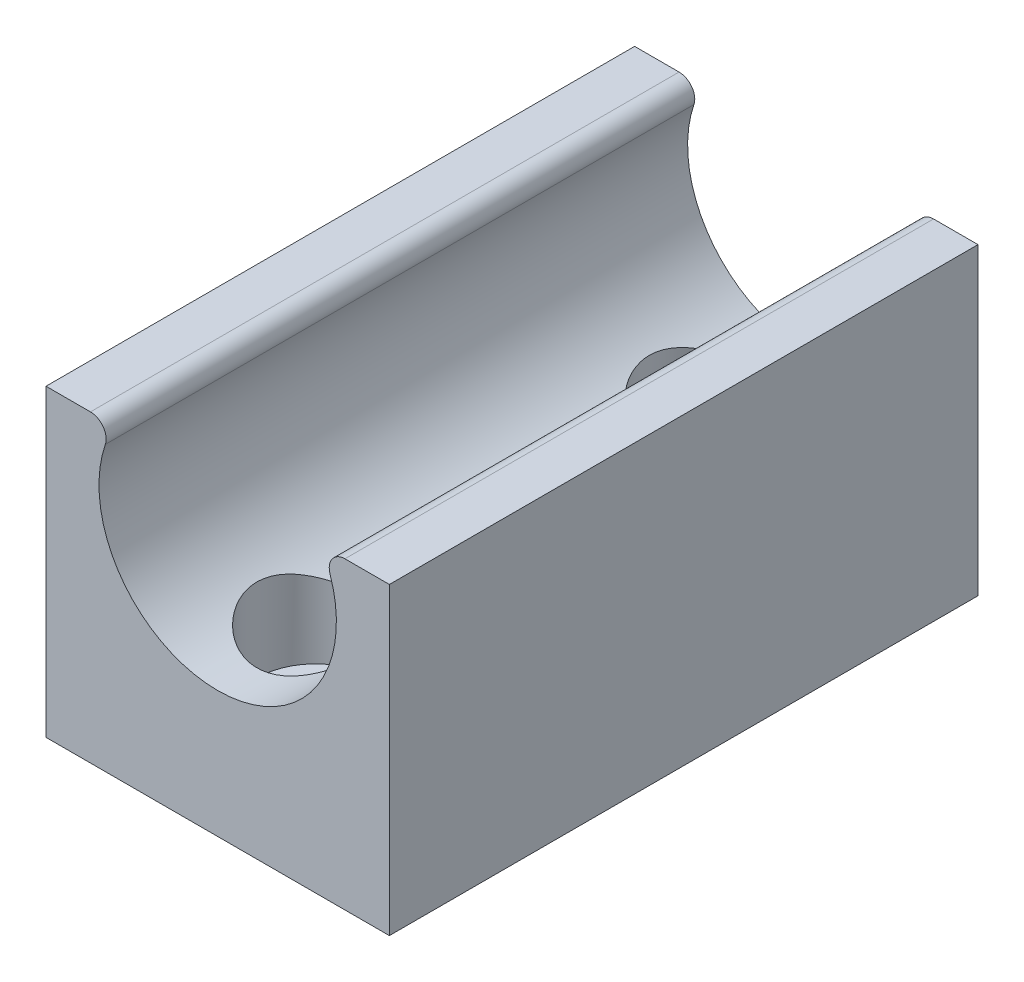
SolidWorks part; units mm, degrees
ref_plane "Front Plane" through (0, 0, 0) normal (0, 0, 1) x (1, 0, 0)
ref_plane "Top Plane" through (0, 0, 0) normal (0, 1, 0) x (1, 0, 0)
ref_plane "Right Plane" through (0, 0, 0) normal (1, 0, 0) x (0, 0, -1)
sketch "Sketch1" plane through (0, 0, 0) normal (0, 0, 1) x (1, 0, 0)
  line L0 (-5.25, 7.75) -> (-8.75, 7.75)
  line L1 (8.75, -7.75) -> (-8.75, -7.75)
  line L2 (8.75, -7.75) -> (8.75, 7.75)
  line L3 (8.75, 7.75) -> (5.25, 7.75)
  line L4 (-8.75, -7.75) -> (-8.75, 7.75)
  line L5 (8.75, -7.75) -> (-8.75, 7.75) construction
  line L6 (8.75, 7.75) -> (-8.75, -7.75) construction
  arc A0 (-5.25, 7.75) -> (5.25, 7.75) centre (0, 4.7433) ccw
  point P0 (0, 0)
  dimension "D1" = 12.1
  dimension "D2" = 3.5
  dimension "D3" = 17.5
  dimension "D4" = 15.5
extrude "Boss-Extrude1" add sketch "Sketch1" along normal blind 30
fillet "Fillet1" radius 0.8 2 edges at (5.25, 7.75, 15) (-5.25, 7.75, 15)
sketch "Sketch3" plane through (0, 7.75, 0) normal (0, 1, 0) x (1, 0, 0)
  line L0 (6.05, 0) -> (-6.05, 0) construction
  line L1 (-6.05, -30) -> (6.05, -30) construction
  circle A0 centre (0, -5) radius 3
  circle A1 centre (0, -25) radius 3
  dimension "D1" = 6
  dimension "D2" = 5
  dimension "D3" = 5
extrude "Cut-Extrude1" cut sketch "Sketch3" against normal blind 12.5
sketch "Sketch4" plane through (0, 7.75, 0) normal (0, 1, 0) x (1, 0, 0)
  circle A0 centre (0, -5) radius 1.55
  circle A1 centre (0, -25) radius 1.55
  dimension "D1" = 3.1
  dimension "D2" = 3.1
extrude "Cut-Extrude2" cut sketch "Sketch4" against normal through all
